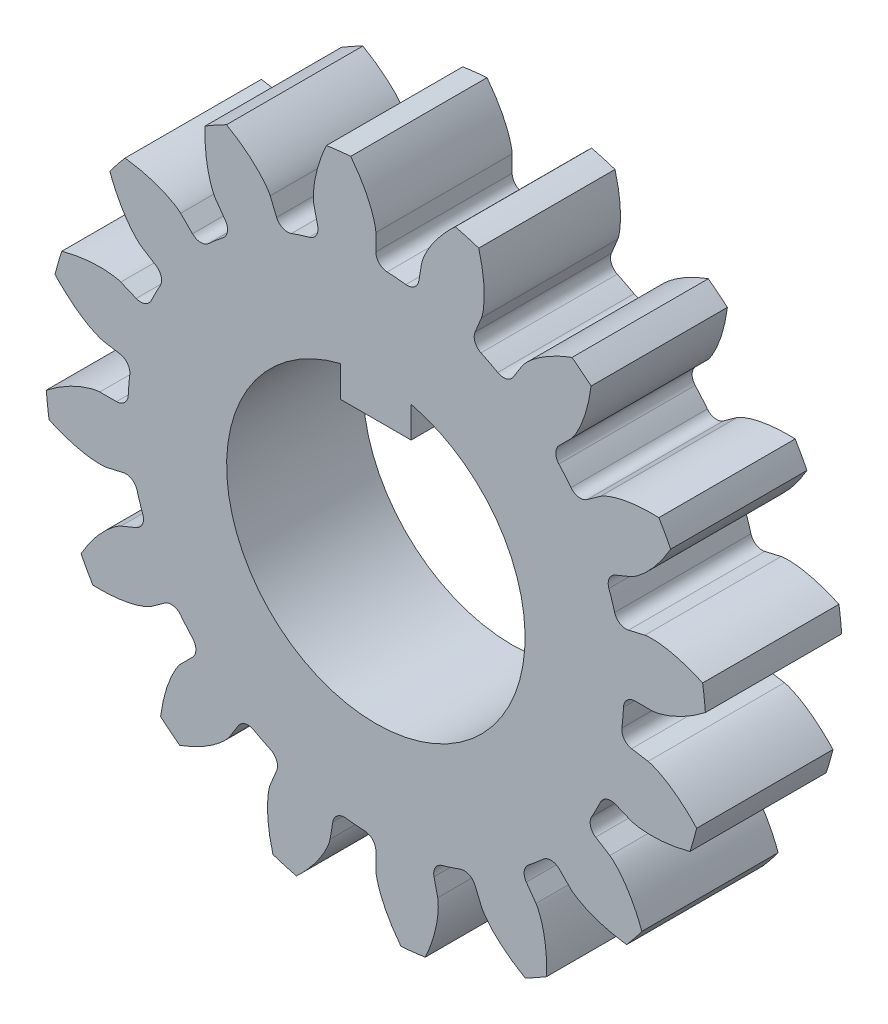
SolidWorks part; units mm, degrees
material "6063-O"
ref_plane "Front Plane" through (0, 0, 0) normal (0, 0, 1) x (1, 0, 0)
ref_plane "Top Plane" through (0, 0, 0) normal (0, 1, 0) x (1, 0, 0)
ref_plane "Right Plane" through (0, 0, 0) normal (1, 0, 0) x (0, 0, -1)
sketch "Sketch1" plane through (0, 0, 0) normal (0, 0, 1) x (1, 0, 0)
  circle A0 centre (0, 0) radius 14.0625
  dimension "D1" = 28.125
extrude "Boss-Extrude1" add sketch "Sketch1" along normal blind 5.8
sketch "Sketch2" plane through (0, 0, 5.8) normal (0, 0, 1) x (1, 0, 0)
  line L0 (10.5469, 0) -> (11.7462, 0)
  line L1 (0, 0) -> (-14.0138, 1.1696) construction
  line L2 (10.4009, -1.7484) -> (11.5836, -1.9472)
  line L3 (0, 0) -> (13.9559, -2.346) construction
  circle A0 centre (0, 0) radius 12.5 construction
  arc A1 (10.4009, -1.7484) -> (10.5469, 0) centre (0, 0) ccw
  circle A2 centre (0, 0) radius 11.7462 construction
  circle A3 centre (0, 0) radius 14.0625 construction
  spline S0 degree 4 poles (11.7462, 0) (11.7502, 0.0001) (11.7614, 0.0004) (11.7827, 0.0017) (11.8174, 0.005) (11.8614, 0.0105) (11.9183, 0.0194) (11.985, 0.032) (12.0581, 0.0481) (12.1374, 0.0681) (12.2161, 0.0902) (12.2942, 0.1142) (12.3718, 0.1399) (12.4653, 0.1732) (12.5769, 0.216) (12.7064, 0.2703) (12.852, 0.3369) (12.999, 0.41) (13.1424, 0.4862) (13.2859, 0.5682) (13.4236, 0.651) (13.565, 0.742) (13.6947, 0.8285) (13.838, 0.9309) (13.9531, 1.0151) (14.1027, 1.1319) (14.1904, 1.2026) (14.2921, 1.2873) (14.3369, 1.3259) (14.3645, 1.3497) knots 0 0 0 0 0 0.005377 0.015084 0.028532 0.04661 0.064855 0.092111 0.119476 0.146842 0.174209 0.201575 0.228941 0.256307 0.307035 0.361767 0.4165 0.471232 0.525964 0.580697 0.635429 0.690161 0.744894 0.799626 0.854358 0.909091 0.954545 1 1 1 1 1 construction
  spline S1 degree 4 poles (11.7462, 0) (11.7502, 0.0001) (11.7614, 0.0004) (11.7827, 0.0017) (11.8174, 0.005) (11.8614, 0.0105) (11.9183, 0.0194) (11.985, 0.032) (12.0581, 0.0481) (12.1374, 0.0681) (12.2161, 0.0902) (12.2942, 0.1142) (12.3718, 0.1399) (12.4653, 0.1732) (12.5769, 0.216) (12.7064, 0.2703) (12.852, 0.3369) (12.999, 0.41) (13.1424, 0.4862) (13.2859, 0.5682) (13.4236, 0.651) (13.565, 0.742) (13.6947, 0.8285) (13.838, 0.9309) (13.9531, 1.0151) (14.0703, 1.1066) (14.127, 1.1518) (14.1559, 1.1751) knots 0 0 0 0 0 0.005377 0.015084 0.028532 0.04661 0.064855 0.092111 0.119476 0.146842 0.174209 0.201575 0.228941 0.256307 0.307035 0.361767 0.4165 0.471232 0.525964 0.580697 0.635429 0.690161 0.744894 0.799626 0.854358 0.909091 0.909091 0.909091 0.909091 0.909091
  spline S2 degree 4 poles (11.5836, -1.9472) (11.5876, -1.9479) (11.5986, -1.9501) (11.6194, -1.955) (11.653, -1.9639) (11.6956, -1.9767) (11.7502, -1.9948) (11.8139, -2.0183) (11.8833, -2.0464) (11.9581, -2.0792) (12.0321, -2.114) (12.1052, -2.1507) (12.1774, -2.1889) (12.2641, -2.2372) (12.3671, -2.2979) (12.4857, -2.3729) (12.6183, -2.4627) (12.7512, -2.5592) (12.88, -2.6582) (13.0079, -2.7628) (13.13, -2.8673) (13.2543, -2.9805) (13.3679, -3.0873) (13.4922, -3.212) (13.5918, -3.3141) (13.7199, -3.4541) (13.7947, -3.5383) (13.881, -3.6387) (13.9188, -3.6842) (13.942, -3.7122) knots 0 0 0 0 0 0.005377 0.015084 0.028532 0.04661 0.064855 0.092111 0.119476 0.146842 0.174209 0.201575 0.228941 0.256307 0.307035 0.361767 0.4165 0.471232 0.525964 0.580697 0.635429 0.690161 0.744894 0.799626 0.854358 0.909091 0.954545 1 1 1 1 1 construction
  spline S3 degree 4 poles (11.5836, -1.9472) (11.5876, -1.9479) (11.5986, -1.9501) (11.6194, -1.955) (11.653, -1.9639) (11.6956, -1.9767) (11.7502, -1.9948) (11.8139, -2.0183) (11.8833, -2.0464) (11.9581, -2.0792) (12.0321, -2.114) (12.1052, -2.1507) (12.1774, -2.1889) (12.2641, -2.2372) (12.3671, -2.2979) (12.4857, -2.3729) (12.6183, -2.4627) (12.7512, -2.5592) (12.88, -2.6582) (13.0079, -2.7628) (13.13, -2.8673) (13.2543, -2.9805) (13.3679, -3.0873) (13.4922, -3.212) (13.5918, -3.3141) (13.6921, -3.4237) (13.7406, -3.4777) (13.7652, -3.5055) knots 0 0 0 0 0 0.005377 0.015084 0.028532 0.04661 0.064855 0.092111 0.119476 0.146842 0.174209 0.201575 0.228941 0.256307 0.307035 0.361767 0.4165 0.471232 0.525964 0.580697 0.635429 0.690161 0.744894 0.799626 0.854358 0.909091 0.909091 0.909091 0.909091 0.909091
  dimension "D1" = 25
  dimension "D2" = 23.4923
  dimension "D3" = 21.0938
  dimension "D4" = 4.771
  dimension "D5" = 4.771
extrude "Cut-Extrude1" cut sketch "Sketch2" against normal through all and the other way through all
fillet "Fillet1" radius 0.5 2 edges at (10.5469, 0, 2.9) (10.4009, -1.7484, 2.9)
pattern_circular "CirPattern19" count 16 over 360 about axis through (0, 0, 5.8) along (0, 0, -1) of "Cut-Extrude1", "Fillet1"
sketch "Sketch3" plane through (0, 0, 0) normal (0, 0, -1) x (-1, 0, 0)
  line L2 (-1.5, 6.1703) -> (-1.5, 4.85)
  line L3 (-1.5, 4.85) -> (1.5, 4.85)
  line L4 (1.5, 6.1703) -> (1.5, 4.85)
  arc A0 (-1.5, 6.1703) -> (1.5, 6.1703) centre (0, 0) ccw
  point P1 (0, 6.35)
  point P4 (0, 4.85)
  dimension "D1" = 12.7
  dimension "D2" = 1.5
extrude "Cut-Extrude2" cut sketch "Sketch3" against normal through all
equation "\"P\"= 0.64'diametrical pitch(mm-1)"
equation "\"N\"= 16'no. of teeth"
equation "\"PA\"= 20deg'pressure angle"
equation "\"a\"= 1 / \"P\"'addendum"
equation "\"d\"= 1.25 / \"P\"'dedendum"
equation "\"c\"= \"d\" - \"a\"'clearence"
equation "\"dp\"= \"N\" / \"P\"'pitch diameter"
equation "\"bd\"= \"dp\" * cos ( \"PA\" )'base diameter"
equation "\"D1@Sketch1\"= \"dp\" + 2 * \"a\"'Addendum circle diameter"
equation "\"D1@Sketch2\"= \"dp\"'pitch diameter"
equation "\"D2@Sketch2\"= \"bd\" 'base circle diameter"
equation "\"D3@Sketch2\"= \"dp\" - 2 * \"d\" 'dedendum circle diameter"
equation "\"alpha\"= sqr ( \"dp\" ^ 2 - \"bd\" ^ 2 ) / \"bd\" * 180 / pi - \"PA\"'alpha"
equation "\"D4@Sketch2\"= 360 / ( 4 * \"N\" ) - \"alpha\" "
equation "\"D5@Sketch2\"= 360 / ( 4 * \"N\" ) - \"alpha\"'beta"
